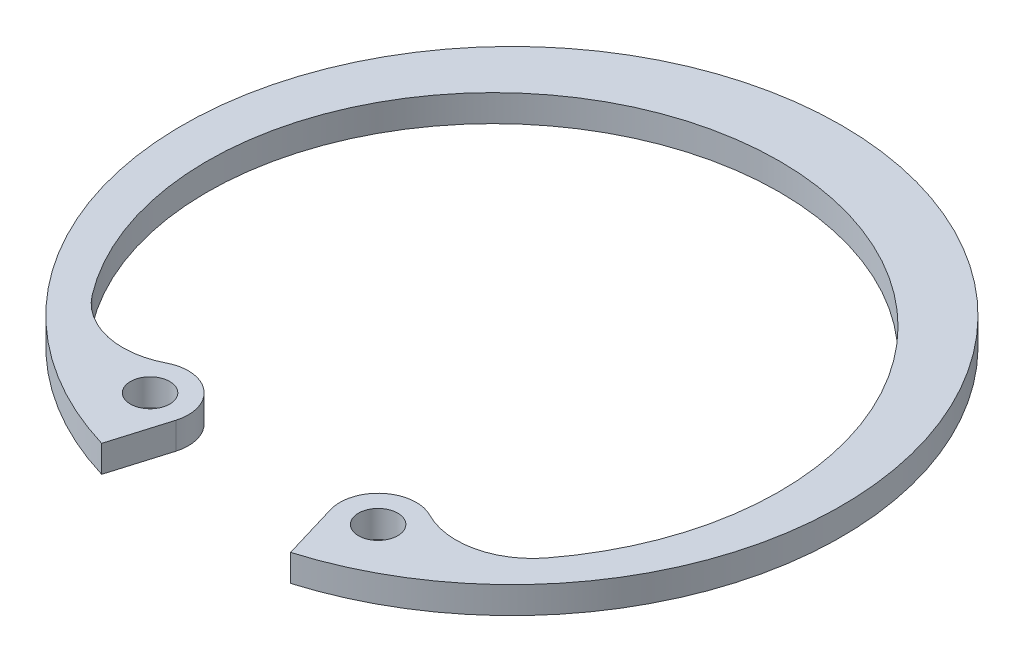
SolidWorks part; units mm, degrees
ref_plane "前视基准面" through (0, 0, 0) normal (0, 0, 1) x (1, 0, 0)
ref_plane "上视基准面" through (0, 0, 0) normal (0, 1, 0) x (1, 0, 0)
ref_plane "右视基准面" through (0, 0, 0) normal (1, 0, 0) x (0, 0, -1)
sketch "草图1" plane through (0, 0, 0) normal (0, 1, 0) x (1, 0, 0)
  line L0 (0, 0) -> (0, -0.9)
  line L1 (0, -0.9) -> (0, -15.95) construction
  line L2 (0, 0) -> (4.5701, -15.2813)
  line L3 (0, 0) -> (-4.5701, -15.2813)
  arc A0 (4.5701, -15.2813) -> (-4.5701, -15.2813) centre (0, 0) ccw
  arc A1 (11.0062, -9.3075) -> (-4.2147, -14.0931) centre (0, -0.9) ccw
  arc A2 (5.5172, -11.9917) -> (-8.8313, -9.8106) centre (0, 0) cw construction
  circle A3 centre (5.5172, -11.9917) radius 0.95
  arc A4 (6.3668, -10.3483) -> (3.7865, -12.6452) centre (5.5172, -11.9917) ccw
  arc A5 (11.0062, -9.3075) -> (6.3668, -10.3483) centre (8.0659, -7.0615) cw
  arc A6 (-11.0062, -9.3075) -> (-6.3668, -10.3483) centre (-8.0659, -7.0615) ccw
  circle A7 centre (-5.5172, -11.9917) radius 0.95
  arc A8 (-6.3668, -10.3483) -> (-3.7865, -12.6452) centre (-5.5172, -11.9917) cw
  dimension "D1" = 31.9
  dimension "D3" = 27.7
  dimension "D5" = 13.2
  dimension "D6" = 1.9
  dimension "D7" = 3.7
  dimension "D8" = 3.7
  dimension "D2" = 0.9
  dimension "D4" = 16.65
extrude "凸台-拉伸1" add sketch "草图1" along normal blind 1.3
